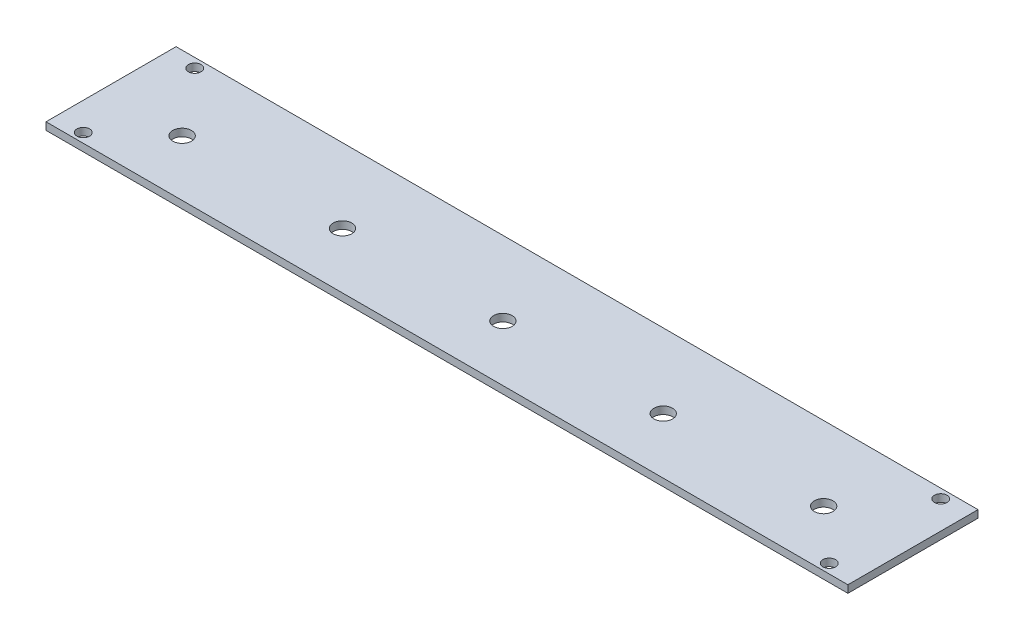
SolidWorks part; units mm, degrees
ref_plane "Front Plane" through (0, 0, 0) normal (0, 0, 1) x (1, 0, 0)
ref_plane "Top Plane" through (0, 0, 0) normal (0, 1, 0) x (1, 0, 0)
ref_plane "Right Plane" through (0, 0, 0) normal (1, 0, 0) x (0, 0, -1)
sketch "Sketch2" plane through (0, 0, 0) normal (0, 1, 0) x (1, 0, 0)
  line L1 (-129.6993, 0.4396) -> (85.4007, 0.4396)
  line L2 (-129.6993, 0.4396) -> (-129.6993, -34.4604)
  line L3 (-129.6993, -34.4604) -> (85.4007, -34.4604)
  line L4 (85.4007, 0.4396) -> (85.4007, -34.4604)
  dimension "D1" = 215.1
  dimension "D2" = 34.9
extrude "Boss-Extrude1" add sketch "Sketch2" along normal blind 2
sketch "Sketch3" plane through (0, 2, 0) normal (0, 1, 0) x (1, 0, 0)
  line L0 (-129.6993, 0.4396) -> (-129.6993, -34.4604) construction
  line L2 (85.4007, 0.4396) -> (-129.6993, 0.4396) construction
  line L3 (85.4007, -34.4604) -> (85.4007, 0.4396) construction
  line L5 (-129.6993, -34.4604) -> (85.4007, -34.4604) construction
  point P0 (-122.1993, -2.0604)
  point P1 (-122.1993, -31.9604)
  point P2 (77.9007, -31.9604)
  point P3 (77.9007, -2.0604)
  dimension "D1" = 7.5
  dimension "D2" = 2.5
  dimension "D3" = 7.5
  dimension "D4" = 2.5
hole_wizard "M3 Clearance Hole1" positions "Sketch4" profile "Sketch5" hole size "M3" standard "ANSI Metric" end condition through all
sketch "Sketch4" plane through (0, 2, 0) normal (0, 1, 0) x (1, 0, 0)
  point P0 (-122.1993, -2.0604)
  point P3 (-122.1993, -31.9604)
  point P6 (77.9007, -2.0604)
  point P9 (77.9007, -31.9604)
sketch "Sketch5" plane through (-122.1993, 2, 2.0604) normal (1, 0, 0) x (0, 0, 1)
  line L0 (0, 0) -> (0, 2)
  line L1 (0, 2) -> (1.7, 2)
  line L2 (1.7, 2) -> (1.7, 0)
  line L5 (1.7, 0) -> (0, 0)
  line L11 (0, -6.35) -> (0, 107.95) construction
  dimension "Thru Hole Dia." = 3.4
  dimension "Thru Hole Depth" = 2
sketch "Sketch7" plane through (0, 0, 0) normal (0, -1, 0) x (1, 0, 0)
  line L1 (-129.6993, 34.4604) -> (85.4007, 34.4604) construction
  line L2 (-129.6993, -0.4396) -> (-129.6993, 34.4604) construction
  circle A0 centre (-108.1893, 19.4604) radius 2.5
  circle A1 centre (-65.1693, 19.4604) radius 2.5
  circle A2 centre (-22.1493, 19.4604) radius 2.5
  circle A3 centre (20.8707, 19.4604) radius 2.5
  circle A4 centre (63.8907, 19.4604) radius 2.5
  point P10 (-189.5133, 19.4604)
  point P11 (0, 0)
  point P12 (-140.2581, 19.4604)
  point P13 (-115.4235, 19.4604)
  dimension "D1" = 5
  dimension "D2" = 5
  dimension "D3" = 5
  dimension "D4" = 5
  dimension "D5" = 5
  dimension "D6" = 21.51
  dimension "D7" = 43.02
  dimension "D8" = 43.02
  dimension "D9" = 43.02
  dimension "D10" = 43.02
  dimension "D11" = 15
extrude "Cut-Extrude1" cut sketch "Sketch7" against normal up to next
